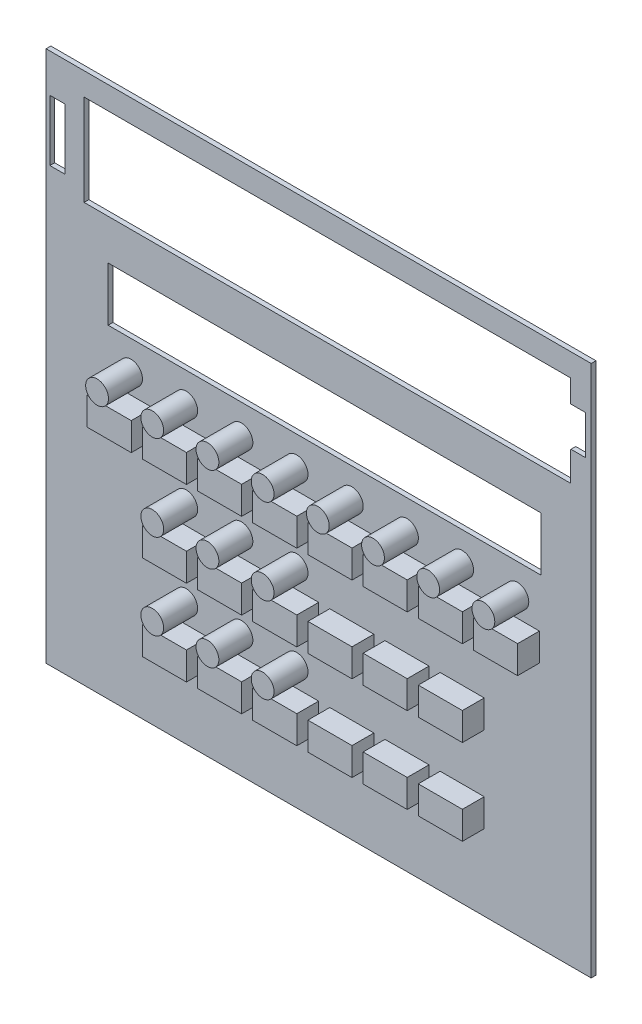
SolidWorks part; units mm, degrees
ref_plane "Front Plane" through (0, 0, 0) normal (0, 0, 1) x (1, 0, 0)
ref_plane "Top Plane" through (0, 0, 0) normal (0, 1, 0) x (1, 0, 0)
ref_plane "Right Plane" through (0, 0, 0) normal (1, 0, 0) x (0, 0, -1)
sketch "Sketch1" plane through (0, 0, 0) normal (0, 0, 1) x (1, 0, 0)
  line L0 (0, 0) -> (0, 177.8)
  line L1 (0, 177.8) -> (182.118, 177.8)
  line L2 (182.118, 177.8) -> (182.118, 0)
  line L3 (182.118, 0) -> (0, 0)
  line L4 (20.7391, 108.1786) -> (20.7391, 126.1796)
  line L5 (20.7391, 126.1796) -> (165.3007, 126.1796)
  line L6 (165.3007, 126.1796) -> (165.3007, 108.1786)
  line L7 (165.3007, 108.1786) -> (20.7391, 108.1786)
  line L8 (1.27, 144.653) -> (1.27, 164.973)
  line L9 (1.27, 164.973) -> (6.35, 164.973)
  line L10 (6.35, 164.973) -> (6.35, 144.653)
  line L11 (6.35, 144.653) -> (1.27, 144.653)
  line L12 (12.7, 139.7) -> (12.7, 170.18)
  line L13 (12.7, 170.18) -> (175.26, 170.18)
  line L14 (175.26, 170.18) -> (175.26, 162.6616)
  line L15 (175.26, 162.6616) -> (180.086, 162.6616)
  line L16 (180.086, 162.6616) -> (180.2892, 162.4584)
  line L17 (180.2892, 162.4584) -> (180.2892, 149.606)
  line L18 (180.2892, 149.606) -> (175.3616, 149.606)
  line L19 (175.3616, 149.606) -> (175.26, 149.5044)
  line L20 (175.26, 149.5044) -> (175.26, 139.7)
  line L21 (175.26, 139.7) -> (12.7, 139.7)
extrude "BOARD" add sketch "Sketch1" along normal blind 1.5921 separate body
ref_plane "Plane1" through (0, 0, 1.5921) normal (0, 0, 1) x (1, 0, 0)
sketch "Sketch2" plane through (0, 0, 1.5921) normal (0, 0, 1) x (1, 0, 0)
  circle A0 centre (83.7097, 41.1988) radius 3.81
extrude "LED-KINGBRIGHT_3P_2P54-1" add sketch "Sketch2" along normal blind 11.3538 separate body
sketch "Sketch3" plane through (0, 0, 1.5921) normal (0, 0, 1) x (1, 0, 0)
  circle A0 centre (65.2722, 41.1988) radius 3.81
extrude "LED-KINGBRIGHT_3P_2P54-2" add sketch "Sketch3" along normal blind 11.3538 separate body
sketch "Sketch4" plane through (0, 0, 1.5921) normal (0, 0, 1) x (1, 0, 0)
  circle A0 centre (46.8347, 41.1988) radius 3.81
extrude "LED-KINGBRIGHT_3P_2P54-3" add sketch "Sketch4" along normal blind 11.3538 separate body
sketch "Sketch6" plane through (0, 0, 1.5921) normal (0, 0, 1) x (1, 0, 0)
  circle A0 centre (83.7097, 69.7738) radius 3.81
extrude "LED-KINGBRIGHT_3P_2P54-5" add sketch "Sketch6" along normal blind 11.3538 separate body
sketch "Sketch7" plane through (0, 0, 1.5921) normal (0, 0, 1) x (1, 0, 0)
  circle A0 centre (65.2722, 69.7738) radius 3.81
extrude "LED-KINGBRIGHT_3P_2P54-6" add sketch "Sketch7" along normal blind 11.3538 separate body
sketch "Sketch8" plane through (0, 0, 1.5921) normal (0, 0, 1) x (1, 0, 0)
  circle A0 centre (46.8347, 69.7738) radius 3.81
extrude "LED-KINGBRIGHT_3P_2P54-7" add sketch "Sketch8" along normal blind 11.3538 separate body
sketch "Sketch10" plane through (0, 0, 1.5921) normal (0, 0, 1) x (1, 0, 0)
  circle A0 centre (157.4597, 98.3488) radius 3.81
extrude "LED-KINGBRIGHT_3P_2P54-9" add sketch "Sketch10" along normal blind 11.3538 separate body
sketch "Sketch11" plane through (0, 0, 1.5921) normal (0, 0, 1) x (1, 0, 0)
  circle A0 centre (139.0222, 98.3488) radius 3.81
extrude "LED-KINGBRIGHT_3P_2P54-10" add sketch "Sketch11" along normal blind 11.3538 separate body
sketch "Sketch12" plane through (0, 0, 1.5921) normal (0, 0, 1) x (1, 0, 0)
  circle A0 centre (120.5847, 98.3488) radius 3.81
extrude "LED-KINGBRIGHT_3P_2P54-11" add sketch "Sketch12" along normal blind 11.3538 separate body
sketch "Sketch13" plane through (0, 0, 1.5921) normal (0, 0, 1) x (1, 0, 0)
  circle A0 centre (102.1472, 98.3488) radius 3.81
extrude "LED-KINGBRIGHT_3P_2P54-12" add sketch "Sketch13" along normal blind 11.3538 separate body
sketch "Sketch14" plane through (0, 0, 1.5921) normal (0, 0, 1) x (1, 0, 0)
  circle A0 centre (83.7097, 98.3488) radius 3.81
extrude "LED-KINGBRIGHT_3P_2P54-13" add sketch "Sketch14" along normal blind 11.3538 separate body
sketch "Sketch15" plane through (0, 0, 1.5921) normal (0, 0, 1) x (1, 0, 0)
  circle A0 centre (65.2722, 98.3488) radius 3.81
extrude "LED-KINGBRIGHT_3P_2P54-14" add sketch "Sketch15" along normal blind 11.3538 separate body
sketch "Sketch16" plane through (0, 0, 1.5921) normal (0, 0, 1) x (1, 0, 0)
  circle A0 centre (46.8347, 98.3488) radius 3.81
extrude "LED-KINGBRIGHT_3P_2P54-15" add sketch "Sketch16" along normal blind 11.3538 separate body
sketch "Sketch17" plane through (0, 0, 1.5921) normal (0, 0, 1) x (1, 0, 0)
  circle A0 centre (28.3972, 98.3488) radius 3.81
extrude "LED-KINGBRIGHT_3P_2P54-16" add sketch "Sketch17" along normal blind 11.3538 separate body
sketch "Sketch18" plane through (0, 0, 1.5921) normal (0, 0, 1) x (1, 0, 0)
  line L0 (131.6562, 25.3238) -> (131.6562, 34.5948)
  line L1 (131.6562, 34.5948) -> (146.3882, 34.5948)
  line L2 (146.3882, 34.5948) -> (146.3882, 25.3238)
  line L3 (146.3882, 25.3238) -> (131.6562, 25.3238)
extrude "SWITCH-MCDTS2-1" add sketch "Sketch18" along normal blind 7.3 separate body
sketch "Sketch19" plane through (0, 0, 1.5921) normal (0, 0, 1) x (1, 0, 0)
  line L0 (113.2187, 25.3238) -> (113.2187, 34.5948)
  line L1 (113.2187, 34.5948) -> (127.9507, 34.5948)
  line L2 (127.9507, 34.5948) -> (127.9507, 25.3238)
  line L3 (127.9507, 25.3238) -> (113.2187, 25.3238)
extrude "SWITCH-MCDTS2-2" add sketch "Sketch19" along normal blind 7.3 separate body
sketch "Sketch20" plane through (0, 0, 1.5921) normal (0, 0, 1) x (1, 0, 0)
  line L0 (94.7812, 25.3238) -> (94.7812, 34.5948)
  line L1 (94.7812, 34.5948) -> (109.5132, 34.5948)
  line L2 (109.5132, 34.5948) -> (109.5132, 25.3238)
  line L3 (109.5132, 25.3238) -> (94.7812, 25.3238)
extrude "SWITCH-MCDTS2-3" add sketch "Sketch20" along normal blind 7.3 separate body
sketch "Sketch21" plane through (0, 0, 1.5921) normal (0, 0, 1) x (1, 0, 0)
  line L0 (76.3437, 25.3238) -> (76.3437, 34.5948)
  line L1 (76.3437, 34.5948) -> (91.0757, 34.5948)
  line L2 (91.0757, 34.5948) -> (91.0757, 25.3238)
  line L3 (91.0757, 25.3238) -> (76.3437, 25.3238)
extrude "SWITCH-MCDTS2-4" add sketch "Sketch21" along normal blind 7.3 separate body
sketch "Sketch22" plane through (0, 0, 1.5921) normal (0, 0, 1) x (1, 0, 0)
  line L0 (57.9062, 25.3238) -> (57.9062, 34.5948)
  line L1 (57.9062, 34.5948) -> (72.6382, 34.5948)
  line L2 (72.6382, 34.5948) -> (72.6382, 25.3238)
  line L3 (72.6382, 25.3238) -> (57.9062, 25.3238)
extrude "SWITCH-MCDTS2-5" add sketch "Sketch22" along normal blind 7.3 separate body
sketch "Sketch23" plane through (0, 0, 1.5921) normal (0, 0, 1) x (1, 0, 0)
  line L0 (39.4687, 25.3238) -> (39.4687, 34.5948)
  line L1 (39.4687, 34.5948) -> (54.2007, 34.5948)
  line L2 (54.2007, 34.5948) -> (54.2007, 25.3238)
  line L3 (54.2007, 25.3238) -> (39.4687, 25.3238)
extrude "SWITCH-MCDTS2-6" add sketch "Sketch23" along normal blind 7.3 separate body
sketch "Sketch25" plane through (0, 0, 1.5921) normal (0, 0, 1) x (1, 0, 0)
  line L0 (131.6562, 53.8988) -> (131.6562, 63.1698)
  line L1 (131.6562, 63.1698) -> (146.3882, 63.1698)
  line L2 (146.3882, 63.1698) -> (146.3882, 53.8988)
  line L3 (146.3882, 53.8988) -> (131.6562, 53.8988)
extrude "SWITCH-MCDTS2-8" add sketch "Sketch25" along normal blind 7.3 separate body
sketch "Sketch26" plane through (0, 0, 1.5921) normal (0, 0, 1) x (1, 0, 0)
  line L0 (113.2187, 53.8988) -> (113.2187, 63.1698)
  line L1 (113.2187, 63.1698) -> (127.9507, 63.1698)
  line L2 (127.9507, 63.1698) -> (127.9507, 53.8988)
  line L3 (127.9507, 53.8988) -> (113.2187, 53.8988)
extrude "SWITCH-MCDTS2-9" add sketch "Sketch26" along normal blind 7.3 separate body
sketch "Sketch27" plane through (0, 0, 1.5921) normal (0, 0, 1) x (1, 0, 0)
  line L0 (94.7812, 53.8988) -> (94.7812, 63.1698)
  line L1 (94.7812, 63.1698) -> (109.5132, 63.1698)
  line L2 (109.5132, 63.1698) -> (109.5132, 53.8988)
  line L3 (109.5132, 53.8988) -> (94.7812, 53.8988)
extrude "SWITCH-MCDTS2-10" add sketch "Sketch27" along normal blind 7.3 separate body
sketch "Sketch28" plane through (0, 0, 1.5921) normal (0, 0, 1) x (1, 0, 0)
  line L0 (76.3437, 53.8988) -> (76.3437, 63.1698)
  line L1 (76.3437, 63.1698) -> (91.0757, 63.1698)
  line L2 (91.0757, 63.1698) -> (91.0757, 53.8988)
  line L3 (91.0757, 53.8988) -> (76.3437, 53.8988)
extrude "SWITCH-MCDTS2-11" add sketch "Sketch28" along normal blind 7.3 separate body
sketch "Sketch29" plane through (0, 0, 1.5921) normal (0, 0, 1) x (1, 0, 0)
  line L0 (57.9062, 53.8988) -> (57.9062, 63.1698)
  line L1 (57.9062, 63.1698) -> (72.6382, 63.1698)
  line L2 (72.6382, 63.1698) -> (72.6382, 53.8988)
  line L3 (72.6382, 53.8988) -> (57.9062, 53.8988)
extrude "SWITCH-MCDTS2-12" add sketch "Sketch29" along normal blind 7.3 separate body
sketch "Sketch30" plane through (0, 0, 1.5921) normal (0, 0, 1) x (1, 0, 0)
  line L0 (39.4687, 53.8988) -> (39.4687, 63.1698)
  line L1 (39.4687, 63.1698) -> (54.2007, 63.1698)
  line L2 (54.2007, 63.1698) -> (54.2007, 53.8988)
  line L3 (54.2007, 53.8988) -> (39.4687, 53.8988)
extrude "SWITCH-MCDTS2-13" add sketch "Sketch30" along normal blind 7.3 separate body
sketch "Sketch32" plane through (0, 0, 1.5921) normal (0, 0, 1) x (1, 0, 0)
  line L0 (150.0937, 82.4738) -> (150.0937, 91.7448)
  line L1 (150.0937, 91.7448) -> (164.8257, 91.7448)
  line L2 (164.8257, 91.7448) -> (164.8257, 82.4738)
  line L3 (164.8257, 82.4738) -> (150.0937, 82.4738)
extrude "SWITCH-MCDTS2-15" add sketch "Sketch32" along normal blind 7.3 separate body
sketch "Sketch33" plane through (0, 0, 1.5921) normal (0, 0, 1) x (1, 0, 0)
  line L0 (131.6562, 82.4738) -> (131.6562, 91.7448)
  line L1 (131.6562, 91.7448) -> (146.3882, 91.7448)
  line L2 (146.3882, 91.7448) -> (146.3882, 82.4738)
  line L3 (146.3882, 82.4738) -> (131.6562, 82.4738)
extrude "SWITCH-MCDTS2-16" add sketch "Sketch33" along normal blind 7.3 separate body
sketch "Sketch34" plane through (0, 0, 1.5921) normal (0, 0, 1) x (1, 0, 0)
  line L0 (113.2187, 82.4738) -> (113.2187, 91.7448)
  line L1 (113.2187, 91.7448) -> (127.9507, 91.7448)
  line L2 (127.9507, 91.7448) -> (127.9507, 82.4738)
  line L3 (127.9507, 82.4738) -> (113.2187, 82.4738)
extrude "SWITCH-MCDTS2-17" add sketch "Sketch34" along normal blind 7.3 separate body
sketch "Sketch35" plane through (0, 0, 1.5921) normal (0, 0, 1) x (1, 0, 0)
  line L0 (94.7812, 82.4738) -> (94.7812, 91.7448)
  line L1 (94.7812, 91.7448) -> (109.5132, 91.7448)
  line L2 (109.5132, 91.7448) -> (109.5132, 82.4738)
  line L3 (109.5132, 82.4738) -> (94.7812, 82.4738)
extrude "SWITCH-MCDTS2-18" add sketch "Sketch35" along normal blind 7.3 separate body
sketch "Sketch36" plane through (0, 0, 1.5921) normal (0, 0, 1) x (1, 0, 0)
  line L0 (76.3437, 82.4738) -> (76.3437, 91.7448)
  line L1 (76.3437, 91.7448) -> (91.0757, 91.7448)
  line L2 (91.0757, 91.7448) -> (91.0757, 82.4738)
  line L3 (91.0757, 82.4738) -> (76.3437, 82.4738)
extrude "SWITCH-MCDTS2-19" add sketch "Sketch36" along normal blind 7.3 separate body
sketch "Sketch37" plane through (0, 0, 1.5921) normal (0, 0, 1) x (1, 0, 0)
  line L0 (57.9062, 82.4738) -> (57.9062, 91.7448)
  line L1 (57.9062, 91.7448) -> (72.6382, 91.7448)
  line L2 (72.6382, 91.7448) -> (72.6382, 82.4738)
  line L3 (72.6382, 82.4738) -> (57.9062, 82.4738)
extrude "SWITCH-MCDTS2-20" add sketch "Sketch37" along normal blind 7.3 separate body
sketch "Sketch38" plane through (0, 0, 1.5921) normal (0, 0, 1) x (1, 0, 0)
  line L0 (39.4687, 82.4738) -> (39.4687, 91.7448)
  line L1 (39.4687, 91.7448) -> (54.2007, 91.7448)
  line L2 (54.2007, 91.7448) -> (54.2007, 82.4738)
  line L3 (54.2007, 82.4738) -> (39.4687, 82.4738)
extrude "SWITCH-MCDTS2-21" add sketch "Sketch38" along normal blind 7.3 separate body
sketch "Sketch39" plane through (0, 0, 1.5921) normal (0, 0, 1) x (1, 0, 0)
  line L0 (21.0312, 82.4738) -> (21.0312, 91.7448)
  line L1 (21.0312, 91.7448) -> (35.7632, 91.7448)
  line L2 (35.7632, 91.7448) -> (35.7632, 82.4738)
  line L3 (35.7632, 82.4738) -> (21.0312, 82.4738)
extrude "SWITCH-MCDTS2-22" add sketch "Sketch39" along normal blind 7.3 separate body
